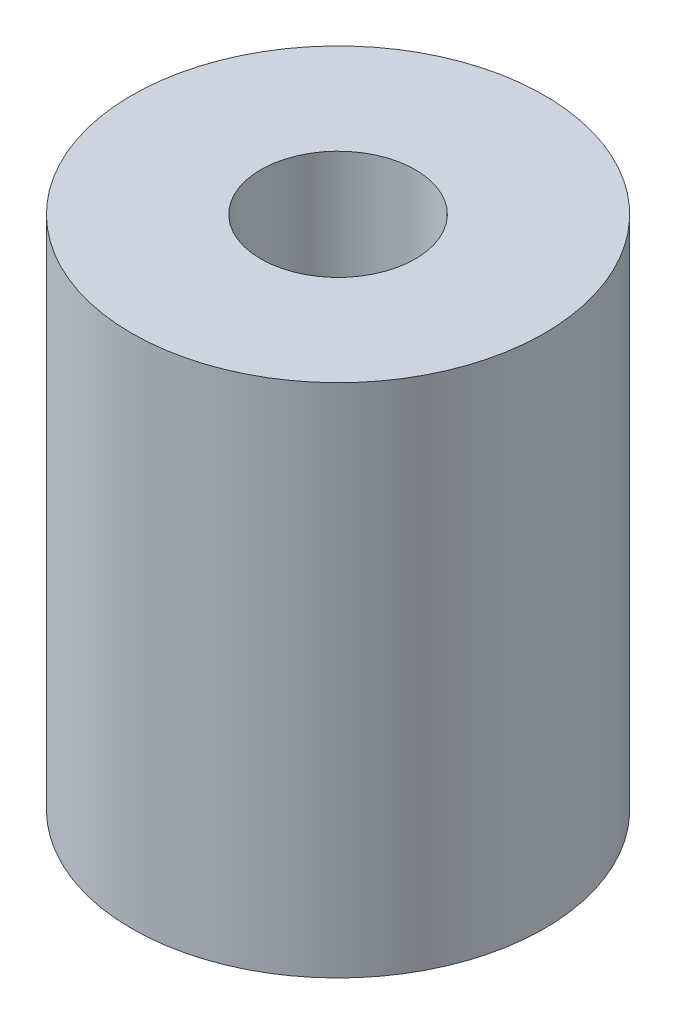
SolidWorks part; units mm, degrees
ref_plane "Front Plane" through (0, 0, 0) normal (0, 0, 1) x (1, 0, 0)
ref_plane "Top Plane" through (0, 0, 0) normal (0, 1, 0) x (1, 0, 0)
ref_plane "Right Plane" through (0, 0, 0) normal (1, 0, 0) x (0, 0, -1)
sketch "Sketch1" plane through (0, 0, 0) normal (0, 1, 0) x (1, 0, 0)
  circle A0 centre (0, 0) radius 4
  dimension "D1" = 8
extrude "Boss-Extrude1" add sketch "Sketch1" along normal blind 10
sketch "Sketch2" plane through (0, 10, 0) normal (0, 1, 0) x (1, 0, 0)
  circle A0 centre (0, 0) radius 1.5
  dimension "D1" = 3
extrude "Cut-Extrude1" cut sketch "Sketch2" against normal through all
